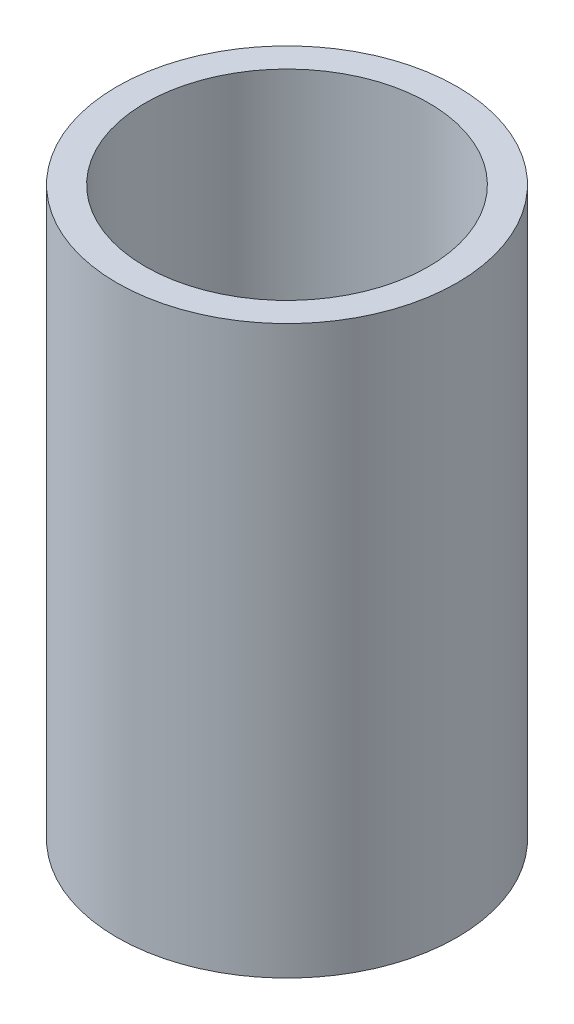
SolidWorks part; units mm, degrees
ref_plane "Спереди" through (0, 0, 0) normal (0, 0, 1) x (1, 0, 0)
ref_plane "Сверху" through (0, 0, 0) normal (0, 1, 0) x (1, 0, 0)
ref_plane "Справа" through (0, 0, 0) normal (1, 0, 0) x (0, 0, -1)
sketch "Эскиз1" plane through (0, 0, 0) normal (0, 1, 0) x (1, 0, 0)
  circle A0 centre (0, 0) radius 12.5
  circle A1 centre (0, 0) radius 15
extrude "Вытянуть1" add sketch "Эскиз1" along normal blind 50
